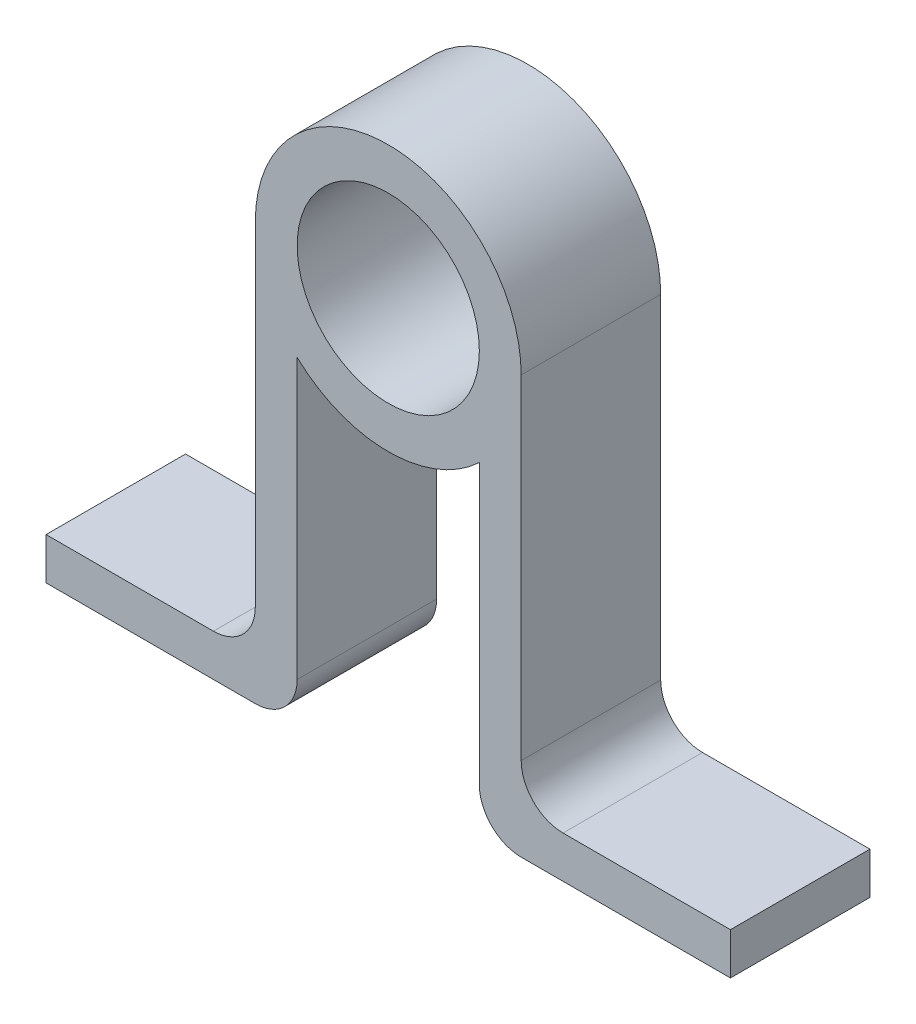
SolidWorks part; units mm, degrees
ref_plane "Front Plane" through (0, 0, 0) normal (0, 0, 1) x (1, 0, 0)
ref_plane "Top Plane" through (0, 0, 0) normal (0, 1, 0) x (1, 0, 0)
ref_plane "Right Plane" through (0, 0, 0) normal (1, 0, 0) x (0, 0, -1)
sketch "Sketch1" plane through (0, 0, 0) normal (0, 0, 1) x (1, 0, 0)
  line L0 (9.53, 0) -> (9.53, -23.94)
  line L1 (12.53, -26.94) -> (24.53, -26.94)
  line L2 (24.53, -26.94) -> (24.53, -29.94)
  line L3 (24.53, -29.94) -> (9.53, -29.94)
  line L4 (6.53, -26.94) -> (6.53, -6.9412)
  line L5 (0, 0) -> (0, -9.53) construction
  line L6 (-6.53, -26.94) -> (-6.53, -6.9412)
  line L7 (-24.53, -29.94) -> (-9.53, -29.94)
  line L8 (-24.53, -26.94) -> (-24.53, -29.94)
  line L9 (-12.53, -26.94) -> (-24.53, -26.94)
  line L10 (-9.53, 0) -> (-9.53, -23.94)
  circle A0 centre (0, 0) radius 6.53
  circle A1 centre (0, 0) radius 9.53
  arc A2 (9.53, -29.94) -> (6.53, -26.94) centre (9.53, -26.94) cw
  arc A3 (12.53, -26.94) -> (9.53, -23.94) centre (12.53, -23.94) cw
  arc A4 (-12.53, -26.94) -> (-9.53, -23.94) centre (-12.53, -23.94) ccw
  arc A5 (-9.53, -29.94) -> (-6.53, -26.94) centre (-9.53, -26.94) ccw
  point P26 (0, 0)
  dimension "D1" = 13.06
  dimension "D5" = 3
  dimension "D3" = 3
  dimension "D4" = 3
  dimension "D6" = 29.94
  dimension "D7" = 15
  dimension "D2" = 3
extrude "Boss-Extrude1" add sketch "Sketch1" along normal blind 10
